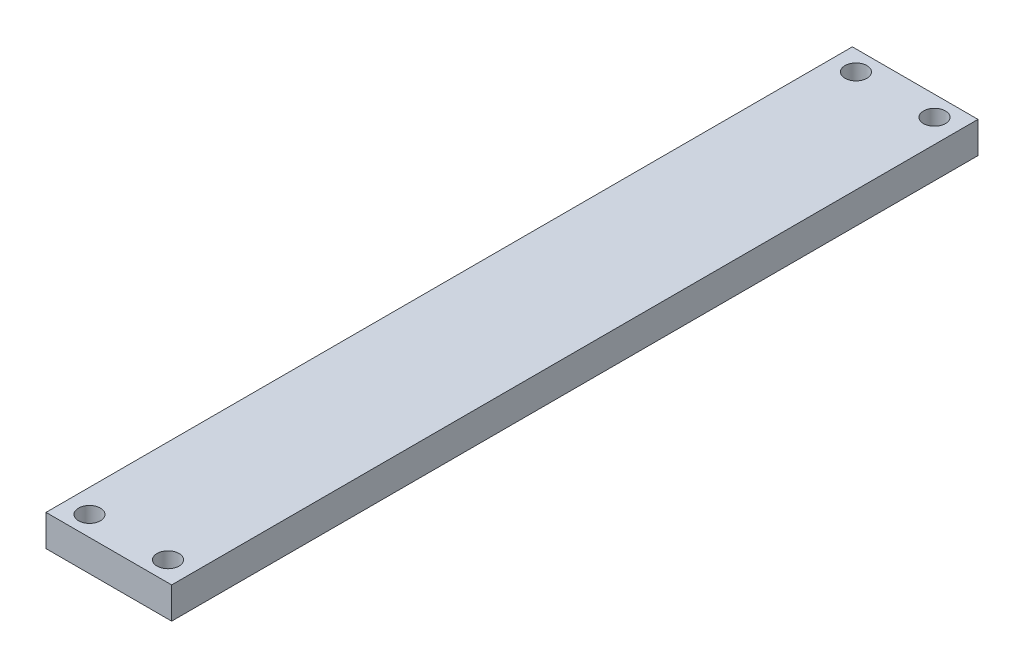
SolidWorks part; units mm, degrees
ref_plane "Front Plane" through (0, 0, 0) normal (0, 0, 1) x (1, 0, 0)
ref_plane "Top Plane" through (0, 0, 0) normal (0, 1, 0) x (1, 0, 0)
ref_plane "Right Plane" through (0, 0, 0) normal (1, 0, 0) x (0, 0, -1)
sketch "Sketch1" plane through (0, 0, 0) normal (0, 0, 1) x (1, 0, 0)
  line L1 (-10, -2.5) -> (10, -2.5)
  line L2 (-10, -2.5) -> (-10, 2.5)
  line L3 (-10, 2.5) -> (10, 2.5)
  line L4 (10, -2.5) -> (10, 2.5)
  line L5 (0, 2.5) -> (0, -2.5) construction
  line L6 (-10, 0) -> (10, 0) construction
  point P0 (0, 0)
  dimension "D1" = 20
  dimension "D2" = 5
extrude "Boss-Extrude1" add sketch "Sketch1" along normal mid plane 128.35
sketch "Sketch2" plane through (0, 2.5, 0) normal (0, 1, 0) x (1, 0, 0)
  line L0 (0, 64.175) -> (0, -64.175) construction
  line L1 (10, 64.175) -> (-10, 64.175) construction
  line L2 (10, -64.175) -> (-10, -64.175) construction
  line L3 (10, 0) -> (-10, 0) construction
  line L4 (10, -64.175) -> (10, 64.175) construction
  line L5 (-10, -64.175) -> (-10, 64.175) construction
  circle A0 centre (-6.25, -61) radius 1.75
  circle A1 centre (6.25, -61) radius 1.75
  circle A2 centre (6.25, 61) radius 1.75
  circle A3 centre (-6.25, 61) radius 1.75
  point P14 (0, 0)
  point P21 (-6.25, -59.5097)
  dimension "D3" = 3.5
  dimension "D1" = 12.5
  dimension "D2" = 12.5
  dimension "D4" = 3.175
extrude "Cut-Extrude1" cut sketch "Sketch2" against normal through all
